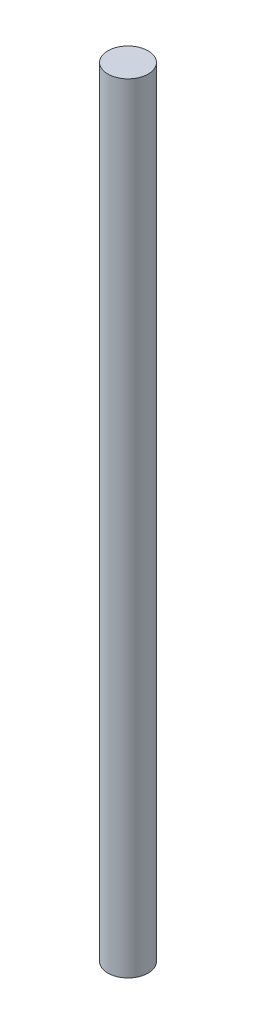
SolidWorks part; units mm, degrees
ref_plane "Front Plane" through (0, 0, 0) normal (0, 0, 1) x (1, 0, 0)
ref_plane "Top Plane" through (0, 0, 0) normal (0, 1, 0) x (1, 0, 0)
ref_plane "Right Plane" through (0, 0, 0) normal (1, 0, 0) x (0, 0, -1)
sketch "Sketch2" plane through (0, 0, 0) normal (0, 1, 0) x (1, 0, 0)
  circle A0 centre (0, 0) radius 22.5
  dimension "D1" = 45
extrude "Boss-Extrude1" add sketch "Sketch2" along normal blind 870
